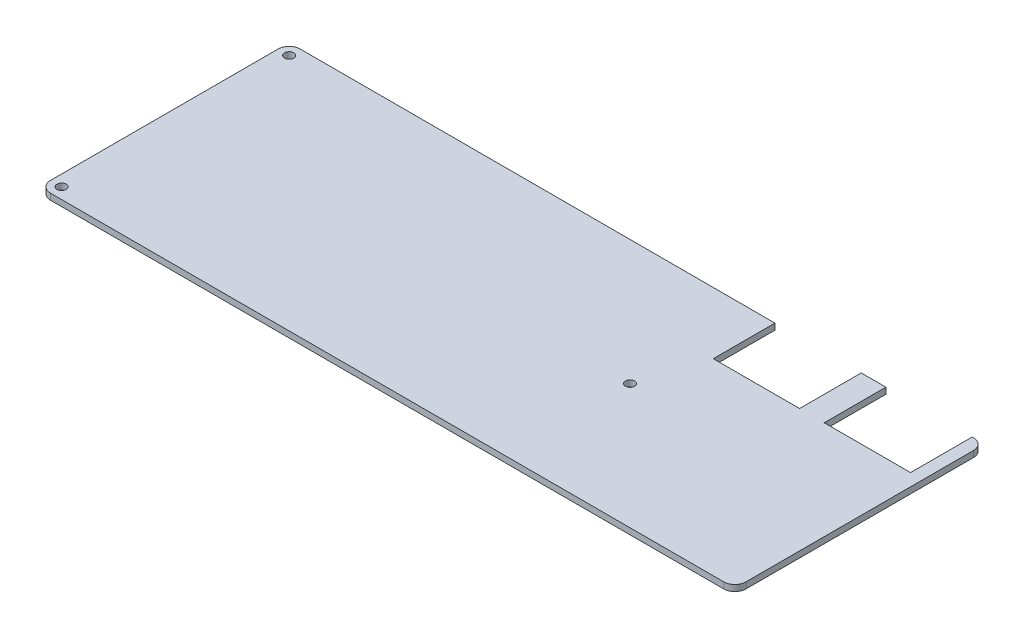
SolidWorks part; units mm, degrees
ref_plane "前视基准面" through (0, 0, 0) normal (0, 0, 1) x (1, 0, 0)
ref_plane "上视基准面" through (0, 0, 0) normal (0, 1, 0) x (1, 0, 0)
ref_plane "右视基准面" through (0, 0, 0) normal (1, 0, 0) x (0, 0, -1)
sketch "草图1" plane through (0, 0, 0) normal (0, 1, 0) x (1, 0, 0)
  line L0 (1.3997, -2.7125) -> (57.7997, -2.7125) construction
  line L1 (-53.2003, 17.5375) -> (55.9997, 17.5375)
  line L2 (-55.0003, 15.7375) -> (-55.0003, -21.1625)
  line L3 (-53.2003, -22.9625) -> (55.9997, -22.9625)
  line L4 (57.7997, 15.7375) -> (57.7997, -21.1625)
  line L5 (-55.0003, 17.5375) -> (57.7997, -22.9625) construction
  line L6 (-55.0003, -22.9625) -> (57.7997, 17.5375) construction
  line L8 (41.7997, 17.5375) -> (55.7997, 17.5375)
  line L9 (41.7997, 17.5375) -> (41.7997, 7.5375)
  line L10 (41.7997, 7.5375) -> (55.7997, 7.5375)
  line L11 (55.7997, 17.5375) -> (55.7997, 7.5375)
  line L12 (41.7997, 17.5375) -> (55.7997, 7.5375) construction
  line L13 (41.7997, 7.5375) -> (55.7997, 17.5375) construction
  line L14 (23.7997, 17.5375) -> (37.7997, 17.5375)
  line L15 (23.7997, 17.5375) -> (23.7997, 7.5375)
  line L16 (23.7997, 7.5375) -> (37.7997, 7.5375)
  line L17 (37.7997, 17.5375) -> (37.7997, 7.5375)
  line L18 (23.7997, 17.5375) -> (37.7997, 7.5375) construction
  line L19 (23.7997, 7.5375) -> (37.7997, 17.5375) construction
  circle A0 centre (-53.2003, 15.7375) radius 1.8 construction
  arc A1 (-55.0003, 15.7375) -> (-53.2003, 17.5375) centre (-53.2003, 15.7375) cw
  arc A2 (55.9997, -22.9625) -> (57.7997, -21.1625) centre (55.9997, -21.1625) ccw
  arc A3 (57.7997, 15.7375) -> (55.9997, 17.5375) centre (55.9997, 15.7375) ccw
  arc A4 (-53.2003, -22.9625) -> (-55.0003, -21.1625) centre (-53.2003, -21.1625) cw
  circle A5 centre (-53.2003, -21.1625) radius 1.8 construction
  circle A6 centre (-53.2003, -21.1625) radius 0.75
  circle A7 centre (-53.2003, 15.7375) radius 0.75
  circle A8 centre (20.5497, -2.7125) radius 1.8 construction
  circle A9 centre (20.5497, -2.7125) radius 0.75
  point P4 (1.3997, -2.7125)
  point P31 (48.7997, 12.5375)
  point P36 (30.7997, 12.5375)
  dimension "D3" = 1.8
  dimension "D4" = 1.8
  dimension "D5" = 37.25
  dimension "D6" = 2
  dimension "D1" = 112.8
  dimension "D2" = 40.5
  dimension "D7" = 4
  dimension "D8" = 14
  dimension "D9" = 14
  dimension "D10" = 10
  dimension "D11" = 10
extrude "凸台-拉伸2" add sketch "草图1" along normal blind 1 contours A4 L3 A2 L4 A3 L1 L11 L10 L9 L17 L16 L15 A1 L2 A9 A7 A6
